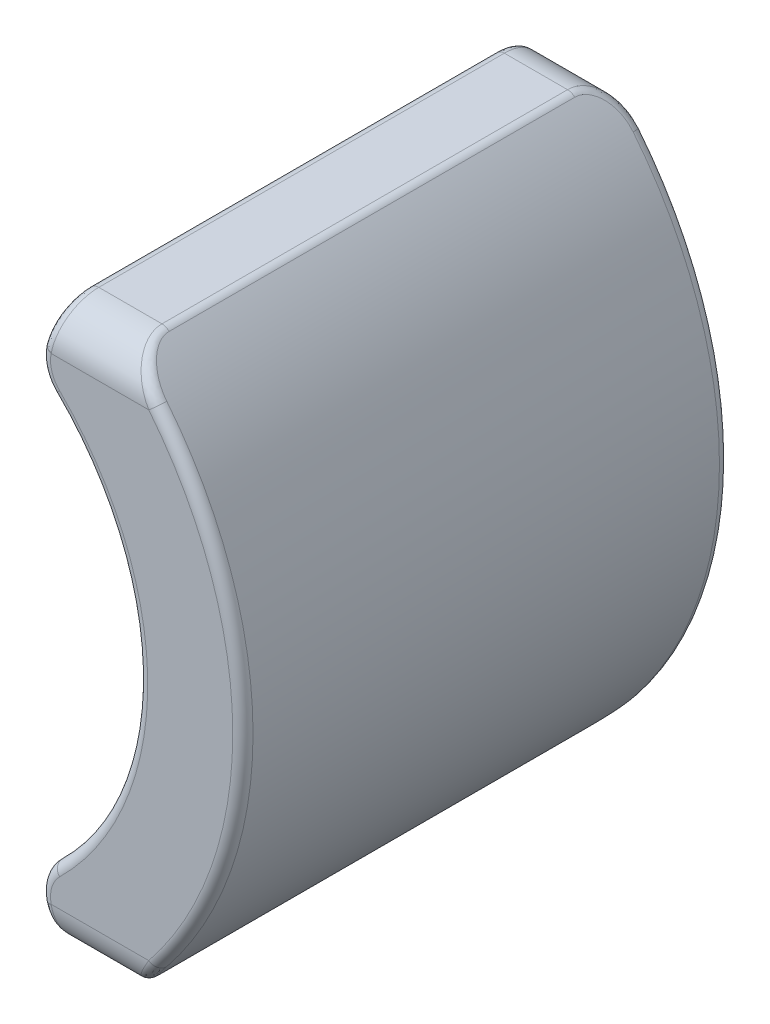
SolidWorks part; units mm, degrees
ref_plane "Front Plane" through (0, 0, 0) normal (0, 0, 1) x (1, 0, 0)
ref_plane "Top Plane" through (0, 0, 0) normal (0, 1, 0) x (1, 0, 0)
ref_plane "Right Plane" through (0, 0, 0) normal (1, 0, 0) x (0, 0, -1)
sketch "Sketch1" plane through (0, 0, 0) normal (0, 0, 1) x (1, 0, 0)
  line L0 (0, 0) -> (9.63, 0) construction
  line L1 (6.7381, -6.88) -> (4.8781, -6.88)
  line L2 (4.8781, -6.88) -> (4.5318, -5.38)
  line L3 (6.7381, 6.88) -> (4.8781, 6.88)
  line L4 (4.8781, 6.88) -> (4.5318, 5.38)
  arc A0 (6.7381, 6.88) -> (6.7381, -6.88) centre (0, 0) cw
  arc A1 (4.5318, 5.38) -> (4.5318, -5.38) centre (0, 0) cw
  point P3 (9.63, 0)
  dimension "D1" = 9.63
  dimension "D2" = 6.88
  dimension "D3" = 1.86
  dimension "D4" = 103
  dimension "D5" = 1.5
extrude "Boss-Extrude1" add sketch "Sketch1" along normal blind 12
fillet "Fillet1" radius 1 2 edges at (4.5318, -5.38, 6) (4.5318, 5.38, 6)
fillet "Fillet2" radius 1 4 edges at (5.8081, -6.88, 12) (5.8081, -6.88, 0) (5.8081, 6.88, 12) (5.8081, 6.88, 0)
fillet "Fillet3" radius 0.25 24 edges at (6.8685, -6.7498, 0.5066) (6.7381, -6.88, 6) (6.9882, -6.6258, 11.6661) (9.63, 0, 12) (6.8685, 6.7498, 11.4934) (6.7381, 6.88, 6) (6.9882, 6.6258, 0.3339) (4.6879, 5.4113, 0) (4.8161, 6.6112, 0.3178) (4.8781, 6.88, 6) (4.8161, 6.6112, 11.6822) (4.6879, 5.4113, 12) (7.0343, 0, 12) (4.6879, -5.4113, 12) (4.8161, -6.6112, 11.6822) (4.8781, -6.88, 6) (4.8161, -6.6112, 0.3178) (4.6879, -5.4113, 0) (9.63, 0, 0) (7.0343, 0, 0)
scale "Scale1" scale about centroid uniform scaling yes scale factor 0.445
